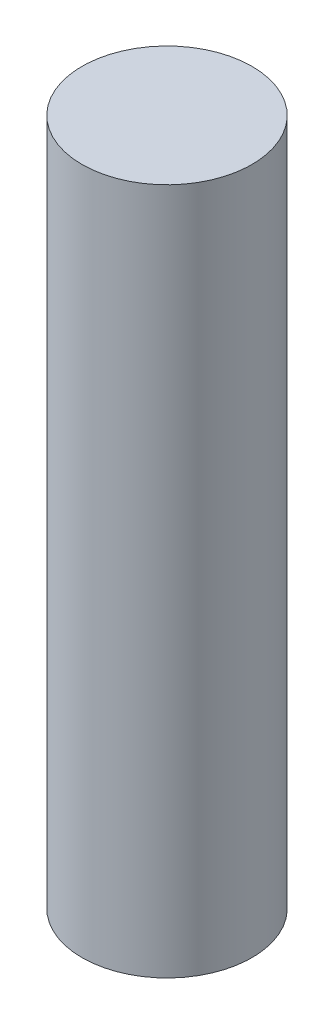
SolidWorks part; units mm, degrees
ref_plane "Front Plane" through (0, 0, 0) normal (0, 0, 1) x (1, 0, 0)
ref_plane "Top Plane" through (0, 0, 0) normal (0, 1, 0) x (1, 0, 0)
ref_plane "Right Plane" through (0, 0, 0) normal (1, 0, 0) x (0, 0, -1)
sketch "Sketch1" plane through (0, 0, 0) normal (0, 1, 0) x (1, 0, 0)
  circle A0 centre (0, 0) radius 2.5
  dimension "D1" = 5
extrude "Boss-Extrude1" add sketch "Sketch1" along normal blind 20.2
